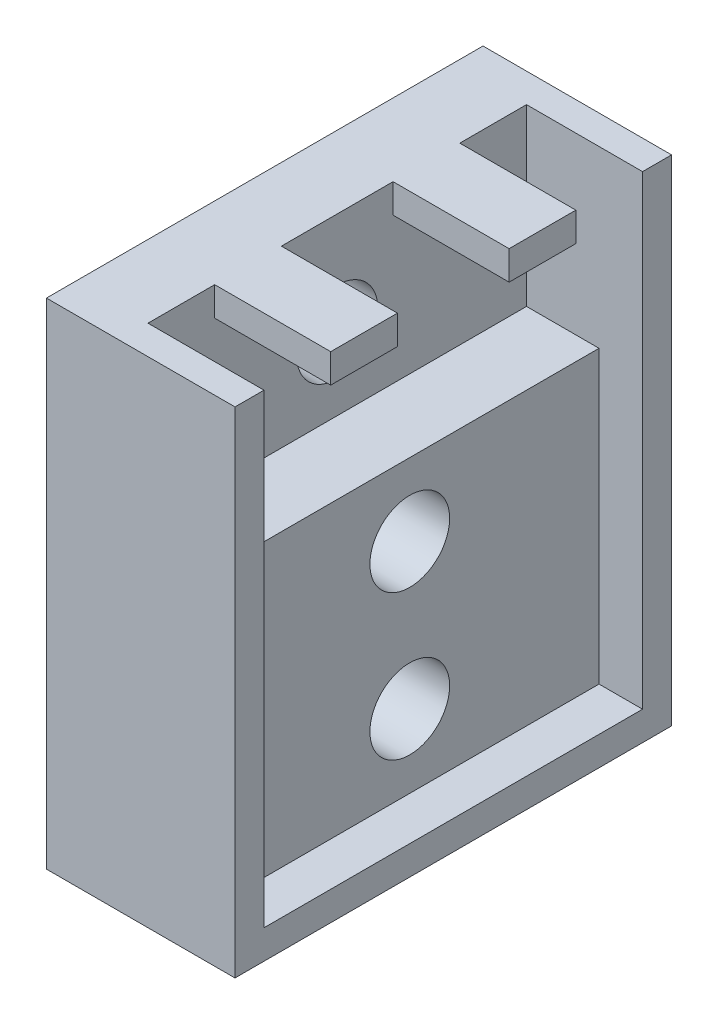
SolidWorks part; units mm, degrees
ref_plane "Front Plane" through (0, 0, 0) normal (0, 0, 1) x (1, 0, 0)
ref_plane "Top Plane" through (0, 0, 0) normal (0, 1, 0) x (1, 0, 0)
ref_plane "Right Plane" through (0, 0, 0) normal (1, 0, 0) x (0, 0, -1)
sketch "Sketch1" plane through (0, 0, 0) normal (1, 0, 0) x (0, 0, -1)
  line L0 (-15.05, 17.05) -> (15.05, 17.05)
  line L1 (-13.05, -15.05) -> (13.05, -15.05)
  line L2 (-13.05, -15.05) -> (-13.05, 15.05)
  line L3 (-13.05, 15.05) -> (13.05, 15.05)
  line L4 (13.05, -15.05) -> (13.05, 15.05)
  line L5 (-13.05, -15.05) -> (13.05, 15.05) construction
  line L6 (-13.05, 15.05) -> (13.05, -15.05) construction
  line L7 (15.05, -17.05) -> (15.05, 17.05)
  line L8 (-15.05, -17.05) -> (15.05, -17.05)
  line L9 (-15.05, -17.05) -> (-15.05, 17.05)
  point P0 (0, 0)
  dimension "D1" = 26.1
  dimension "D2" = 30.1
  dimension "D3" = 2
extrude "Boss-Extrude1" add sketch "Sketch1" along normal blind 5 contours L1 L4 L3 L2 | L9 L8 L7 L0 L4 L1 L2 L3
sketch "Sketch2" plane through (5, 0, 0) normal (1, 0, 0) x (0, 0, -1)
  line L0 (-13.05, 15.05) -> (-13.05, -15.05)
  line L1 (-15.05, 17.05) -> (-13.05, 17.05)
  line L2 (-15.05, 17.05) -> (-15.05, -17.05)
  line L3 (-15.05, -17.05) -> (2.25, -17.05)
  line L4 (15.05, 17.05) -> (15.05, -17.05)
  line L5 (-13.05, -15.05) -> (2.25, -15.05)
  line L6 (13.05, 15.05) -> (13.05, -15.05)
  line L7 (-8.45, 15.05) -> (-3.85, 15.05)
  line L8 (13.05, -15.05) -> (13.05, -17.05)
  line L9 (-13.05, 15.05) -> (-13.05, 17.05)
  line L10 (13.05, 15.05) -> (13.05, 17.05)
  line L11 (2.25, -15.05) -> (2.25, -17.05)
  line L12 (-8.45, 17.05) -> (-8.45, 15.05)
  line L13 (8.45, 17.05) -> (8.45, 15.05)
  line L14 (-3.85, 17.05) -> (-3.85, 15.05)
  line L15 (3.85, 17.05) -> (3.85, 15.05)
  line L16 (3.85, 17.05) -> (8.45, 17.05)
  line L17 (-15.05, 17.05) -> (15.05, 17.05) construction
  line L18 (3.85, 15.05) -> (8.45, 15.05)
  line L19 (-13.05, 15.05) -> (13.05, 15.05) construction
  line L20 (-8.45, 17.05) -> (-3.85, 17.05)
  line L21 (-13.05, -15.05) -> (13.05, -15.05) construction
  line L22 (13.05, -17.05) -> (15.05, -17.05)
  line L23 (-15.05, -17.05) -> (15.05, -17.05) construction
  line L24 (13.05, 17.05) -> (15.05, 17.05)
  line L25 (2.25, -15.05) -> (13.05, -15.05)
  line L26 (13.05, -17.05) -> (2.25, -17.05)
  line M18 (-15.05, 17.05) -> (-15.05, -17.05)
  line M19 (-15.05, -17.05) -> (15.05, -17.05)
  line M20 (15.05, -17.05) -> (15.05, 17.05)
  line M21 (15.05, 17.05) -> (-15.05, 17.05)
  dimension "D1" = 2
  dimension "D2" = 10.8
  dimension "D3" = 4.6
  dimension "D4" = 4.6
  dimension "D5" = 4.6
  dimension "D6" = 4.6
extrude "Boss-Extrude2" add sketch "Sketch2" along normal blind 8 contours L25 L11 L8 M19 | L10 L6 L8 M19 M20 M21 | L15 L18 L13 M21 | L14 L12 L7 M21 | L11 L5 L0 L9 M21 M18 M19
sketch "Sketch3" plane through (5, 0, 0) normal (1, 0, 0) x (0, 0, -1)
  line L0 (-13.05, -15.05) -> (13.05, -15.05) construction
  line L3 (13.05, -15.05) -> (13.05, 17.05) construction
  circle A0 centre (0, -10) radius 1.7
  circle A3 centre (0, 0) radius 1.7
  circle A4 centre (0, 10) radius 1.7
  dimension "D1" = 3.4
  dimension "D5" = 13.05
  dimension "D4" = 5.05
  dimension "D2" = 3
extrude "Cut-Extrude1" cut sketch "Sketch3" against normal through all
sketch "Sketch4" plane through (5, 0, 0) normal (1, 0, 0) x (0, 0, -1)
  circle A0 centre (0, -10) radius 2.8
  circle A1 centre (0, 0) radius 2.8
  circle A2 centre (0, 10) radius 2.8
  dimension "D1" = 5.6
  dimension "D2" = 3
extrude "Cut-Extrude2" cut sketch "Sketch4" against normal blind 3
sketch "Sketch6" plane through (5, 0, 0) normal (1, 0, 0) x (0, 0, -1)
  line L0 (0, 10) -> (0, 0) construction
  line L1 (-13.05, 17.05) -> (-13.05, -15.05) construction
  line L2 (-13.05, 5) -> (13.05, 5)
  line L3 (-13.05, 5) -> (-13.05, -15.05)
  line L4 (-13.05, -15.05) -> (13.05, -15.05)
  line L5 (13.05, 5) -> (13.05, -15.05)
  circle A0 centre (0, 0) radius 2.75
  circle A1 centre (0, -10) radius 2.75
extrude "Boss-Extrude3" add sketch "Sketch6" along normal blind 5
